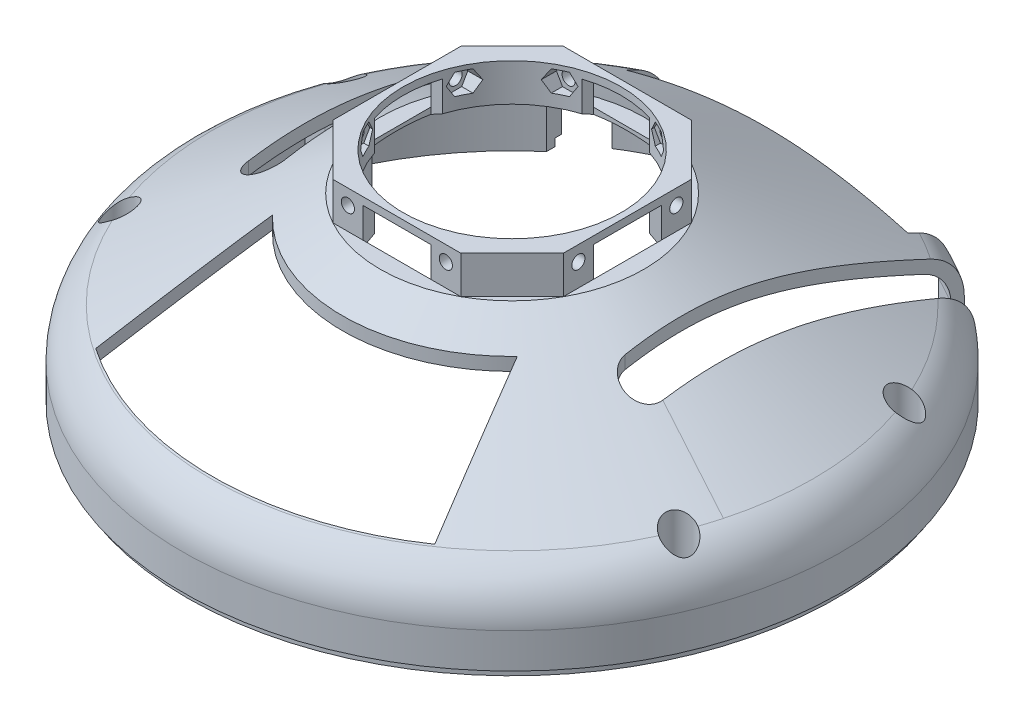
SolidWorks part; units mm, degrees
ref_plane "Front Plane" through (0, 0, 0) normal (0, 0, 1) x (1, 0, 0)
ref_plane "Top Plane" through (0, 0, 0) normal (0, 1, 0) x (1, 0, 0)
ref_plane "Right Plane" through (0, 0, 0) normal (1, 0, 0) x (0, 0, -1)
sketch "Sketch1" plane through (0, 0, 0) normal (0, 0, 1) x (1, 0, 0)
  line L0 (0, 0) -> (-87.5, 0)
  line L1 (-87.5, 0) -> (-87.5, 11.2952)
  line L2 (-79.9421, 24.3188) -> (-35, 50)
  line L3 (-35, 50) -> (0, 50)
  line L4 (0, 50) -> (0, 0)
  arc A0 (-87.5, 11.2952) -> (-79.9421, 24.3188) centre (-72.5, 11.2952) cw
  point P8 (-87.5, 20)
  dimension "D5" = 15
  dimension "D1" = 87.5
  dimension "D2" = 50
  dimension "D3" = 20
  dimension "D4" = 35
revolve "Revolve1" add sketch "Sketch1" angle 360 about L4
shell "Shell2" thickness 3
sketch "Sketch4" plane through (0, 0, 0) normal (0, 1, 0) x (1, 0, 0)
  line L1 (-37.5, 107.5) -> (37.5, 107.5)
  line L2 (-37.5, 107.5) -> (-37.5, 67.5)
  line L3 (-37.5, 67.5) -> (37.5, 67.5)
  line L4 (37.5, 107.5) -> (37.5, 67.5)
  line L5 (-37.5, 107.5) -> (37.5, 67.5) construction
  line L6 (-37.5, 67.5) -> (37.5, 107.5) construction
  circle A0 centre (0, 0) radius 87.5 construction
  point P0 (0, 87.5)
  dimension "D1" = 75
  dimension "D2" = 40
extrude "Cut-Extrude2" cut sketch "Sketch4" along normal through all
sketch "Sketch5" plane through (0, 0, 0) normal (0, -1, 0) x (1, 0, 0)
  circle A0 centre (0, 0) radius 86
  arc A1 (37.5, -79.0569) -> (-37.5, -79.0569) centre (0, 0) ccw construction
  dimension "D1" = 1.5
extrude "Cut-Extrude3" cut sketch "Sketch5" against normal blind 2
sketch "Sketch7" plane through (0, 0, 0) normal (0, -1, 0) x (1, 0, 0)
  line L0 (-74.1747, 29.9685) -> (0, 0) construction
  line L1 (0, 0) -> (-74.1747, 0) construction
  line L2 (-71.0454, 33.8682) -> (-75.68, 37.5872)
  line L3 (-75.68, 37.5872) -> (-80.5498, 25.5338) construction
  line L4 (-80.5498, 25.5338) -> (-74.6326, 24.9895)
  line L5 (-78.1149, 31.5605) -> (-74.1747, 29.9685) construction
  circle A0 centre (-74.1747, 29.9685) radius 1.75
  arc A1 (-74.6326, 24.9895) -> (-71.0454, 33.8682) centre (-74.1747, 29.9685) ccw
  arc A3 (-75.68, 37.5872) -> (-80.5498, 25.5338) centre (0, 0) ccw
  arc A4 (37.5, -75.7232) -> (-37.5, -75.7232) centre (0, 0) ccw construction
  point P15 (-74.1747, 0)
  dimension "D2" = 3.5
  dimension "D3" = 10
  dimension "D1" = 80
  dimension "D4" = 22
  dimension "D5" = 13
extrude "Boss-Extrude1" add sketch "Sketch7" against normal up to next
sketch "Sketch8" plane through (0, 50, 0) normal (0, 1, 0) x (1, 0, 0)
  circle A0 centre (-74.1747, -29.9685) radius 4
  circle A1 centre (-74.1747, -29.9685) radius 1.75 construction
  circle A2 centre (-74.1747, -29.9685) radius 1.75 construction
  dimension "D2" = 8
extrude "Cut-Extrude4" cut sketch "Sketch8" against normal blind 43
mirror "Mirror1" about plane through (0, 0, 0) normal (1, 0, 0) of "Boss-Extrude1", "Cut-Extrude4" second plane through (0, 0, 0) second plane normal (0, 0, 1)
sketch "Sketch9" plane through (0, 0, 0) normal (0, 1, 0) x (1, 0, 0)
  line L0 (-50, 82.5) -> (-50, -15) construction
  line L1 (-45, 82.5) -> (-45, -15)
  line L2 (-55, 82.5) -> (-55, -15)
  line L3 (50, -15) -> (50, 82.5) construction
  line L4 (45, -15) -> (45, 82.5)
  line L5 (55, -15) -> (55, 82.5)
  line L6 (-50, 82.5) -> (50, 82.5) construction
  line L7 (-50, -15) -> (50, -15) construction
  line L8 (0, 0) -> (0, -15) construction
  line L9 (37.5, 67.5) -> (-37.5, 67.5) construction
  arc A0 (-45, 82.5) -> (-55, 82.5) centre (-50, 82.5) ccw
  arc A1 (-55, -15) -> (-45, -15) centre (-50, -15) ccw
  arc A2 (45, -15) -> (55, -15) centre (50, -15) ccw
  arc A3 (55, 82.5) -> (45, 82.5) centre (50, 82.5) ccw
  point P2 (-50, 33.75)
  point P7 (50, 33.75)
  dimension "D1" = 100
  dimension "D2" = 15
  dimension "D3" = 10
  dimension "D4" = 15
extrude "Cut-Extrude5" cut sketch "Sketch9" along normal through all
sketch "Sketch10" plane through (0, 0, 0) normal (0, 1, 0) x (1, 0, 0)
  line L0 (-32.5, -31.1247) -> (-45, -65.5382)
  line L1 (-45, -65.5382) -> (45, -65.5382) construction
  line L2 (45, -65.5382) -> (32.5, -31.1247)
  line L3 (32.5, -31.1247) -> (-32.5, -31.1247) construction
  arc A0 (-32.5, -31.1247) -> (32.5, -31.1247) centre (0, 0) ccw
  arc A1 (-45, -65.5382) -> (45, -65.5382) centre (0, 0) ccw
  arc A2 (-55, 68.0533) -> (55, 68.0533) centre (0, 0) ccw construction
  circle A4 centre (0, 0) radius 35 construction
  dimension "D1" = 8
  dimension "D2" = 10
  dimension "D3" = 90
  dimension "D4" = 65
extrude "Cut-Extrude6" cut sketch "Sketch10" along normal through all
sketch "Sketch11" plane through (0, 50, 0) normal (0, 1, 0) x (1, 0, 0)
  line L1 (-17, 30.5941) -> (-30.5941, 17)
  line L2 (-30.5941, 17) -> (-30.5941, -17)
  line L3 (-30.5941, -17) -> (-17, -30.5941)
  line L4 (-17, -30.5941) -> (17, -30.5941)
  line L5 (17, -30.5941) -> (30.5941, -17)
  line L6 (30.5941, -17) -> (30.5941, 17)
  line L7 (30.5941, 17) -> (17, 30.5941)
  line L8 (17, 30.5941) -> (-17, 30.5941)
  circle A0 centre (0, 0) radius 28.9533 construction
  circle A3 centre (0, 0) radius 28.9533
  circle A4 centre (0, 0) radius 35 construction
  dimension "D1" = 34
extrude "Boss-Extrude2" add sketch "Sketch11" along normal blind 10
sketch "Sketch13" plane through (0, 0, 30.5941) normal (0, 0, 1) x (1, 0, 0)
  line L0 (0, 58) -> (0, 60) construction
  line L1 (-9, 58) -> (9, 58)
  line L2 (-9, 58) -> (-9, 48)
  line L3 (-9, 48) -> (9, 48)
  line L4 (9, 58) -> (9, 48)
  line L5 (-9, 58) -> (9, 48) construction
  line L6 (-9, 48) -> (9, 58) construction
  line L7 (-17, 60) -> (17, 60) construction
  line L8 (-13, 56) -> (13, 56) construction
  line L9 (0, 56) -> (0, 58) construction
  circle A0 centre (-13, 56) radius 1.75
  circle A1 centre (13, 56) radius 1.75
  point P0 (0, 53)
  dimension "D2" = 3.5
  dimension "D1" = 26
  dimension "D3" = 4
  dimension "D4" = 2
  dimension "D5" = 18
  dimension "D6" = 10
extrude "Cut-Extrude7" cut sketch "Sketch13" against normal blind 10
sketch "Sketch14" plane through (0, 0, 0) normal (0, 0, 1) x (1, 0, 0)
  line L1 (-9.7668, 56) -> (-11.3834, 58.8)
  line L2 (-11.3834, 58.8) -> (-14.6166, 58.8)
  line L3 (-14.6166, 58.8) -> (-16.2332, 56)
  line L4 (-16.2332, 56) -> (-14.6166, 53.2)
  line L5 (-14.6166, 53.2) -> (-11.3834, 53.2)
  line L6 (-11.3834, 53.2) -> (-9.7668, 56)
  line L7 (16.2332, 56) -> (14.6166, 58.8)
  line L8 (14.6166, 58.8) -> (11.3834, 58.8)
  line L9 (11.3834, 58.8) -> (9.7668, 56)
  line L10 (9.7668, 56) -> (11.3834, 53.2)
  line L11 (11.3834, 53.2) -> (14.6166, 53.2)
  line L12 (14.6166, 53.2) -> (16.2332, 56)
  circle A0 centre (-13, 56) radius 2.8 construction
  circle A1 centre (13, 56) radius 2.8 construction
  dimension "D1" = 5.6
extrude "Cut-Extrude8" cut sketch "Sketch14" along normal blind 28
pattern_circular "CirPattern1" count 4 over 360 about axis through (0, 0, 0) along (0, 1, 0) of "Cut-Extrude7", "Cut-Extrude8"
sketch "Sketch15" plane through (0, 2, 0) normal (0, -1, 0) x (1, 0, 0)
  line L0 (45, -73.2871) -> (45, -71.521) construction
  line L1 (37.5, -75.7232) -> (37.5, -77.3935) construction
  line L2 (-55, -66.1135) -> (-55, -64.1502)
  line L3 (55, -64.1502) -> (55, -66.1135)
  line L4 (-55, -66.1135) -> (-55, -64.1502)
  line L5 (55, -64.1502) -> (55, -66.1135)
  line L6 (-45, -71.521) -> (-45, -73.2871) construction
  line L7 (-37.5, -77.3935) -> (-37.5, -75.7232) construction
  line L8 (45, -73.2871) -> (45, -71.521)
  line L9 (37.5, -75.7232) -> (37.5, -77.3935)
  line L10 (-45, -71.521) -> (-45, -73.2871)
  line L11 (-37.5, -77.3935) -> (-37.5, -75.7232)
  arc A0 (37.5, -77.3935) -> (45, -73.2871) centre (0, 0) ccw construction
  arc A1 (37.5, -75.7232) -> (45, -71.521) centre (0, 0) ccw construction
  arc A2 (-45, -71.521) -> (-37.5, -75.7232) centre (0, 0) ccw construction
  arc A3 (-45, -73.2871) -> (-37.5, -77.3935) centre (0, 0) ccw construction
  arc A4 (37.5, -77.3935) -> (45, -73.2871) centre (0, 0) ccw
  arc A5 (37.5, -75.7232) -> (45, -71.521) centre (0, 0) ccw
  arc A6 (-45, -71.521) -> (-37.5, -75.7232) centre (0, 0) ccw
  arc A7 (-45, -73.2871) -> (-37.5, -77.3935) centre (0, 0) ccw
  arc A9 (55, -66.1135) -> (-55, -66.1135) centre (0, 0) ccw
  arc A10 (-75.68, -37.5872) -> (-55, -64.1502) centre (0, 0) ccw
  arc A11 (-80.5498, -25.5338) -> (-75.68, -37.5872) centre (0, 0) ccw
  arc A12 (-80.5498, 25.5338) -> (-80.5498, -25.5338) centre (0, 0) ccw
  arc A13 (-75.68, 37.5872) -> (-80.5498, 25.5338) centre (0, 0) ccw
  arc A14 (75.68, 37.5872) -> (-75.68, 37.5872) centre (0, 0) ccw
  arc A15 (80.5498, 25.5338) -> (75.68, 37.5872) centre (0, 0) ccw
  arc A16 (80.5498, -25.5338) -> (80.5498, 25.5338) centre (0, 0) ccw
  arc A17 (55, -64.1502) -> (75.68, -37.5872) centre (0, 0) ccw
  arc A18 (55, -66.1135) -> (-55, -66.1135) centre (0, 0) ccw
  arc A19 (-75.68, -37.5872) -> (-55, -64.1502) centre (0, 0) ccw
  arc A20 (-80.5498, -25.5338) -> (-75.68, -37.5872) centre (0, 0) ccw
  arc A21 (-80.5498, 25.5338) -> (-80.5498, -25.5338) centre (0, 0) ccw
  arc A22 (-75.68, 37.5872) -> (-80.5498, 25.5338) centre (0, 0) ccw
  arc A23 (75.68, 37.5872) -> (-75.68, 37.5872) centre (0, 0) ccw
  arc A24 (80.5498, 25.5338) -> (75.68, 37.5872) centre (0, 0) ccw
  arc A25 (80.5498, -25.5338) -> (80.5498, 25.5338) centre (0, 0) ccw
  arc A26 (55, -64.1502) -> (75.68, -37.5872) centre (0, 0) ccw
  arc A28 (75.68, -37.5872) -> (80.5498, -25.5338) centre (0, 0) ccw
  arc A29 (75.68, -37.5872) -> (80.5498, -25.5338) centre (0, 0) ccw
  dimension "D1" = 0
extrude "Boss-Extrude3" add sketch "Sketch15" along normal blind 2
sketch "Sketch16" plane through (0, 0, 0) normal (0, -1, 0) x (1, 0, 0)
  line L0 (55, -64.1502) -> (55, -68.0533) construction
  line L1 (-55, -68.0533) -> (-55, -66.3735)
  line L2 (55, -66.3735) -> (55, -68.0533)
  line L3 (45, -75.0417) -> (45, -71.521) construction
  line L4 (37.5, -75.7232) -> (37.5, -79.0569) construction
  line L5 (-37.5, -79.0569) -> (-37.5, -75.7232) construction
  line L6 (-45, -71.521) -> (-45, -75.0417) construction
  line L7 (45, -75.0417) -> (45, -71.521)
  line L8 (37.5, -75.7232) -> (37.5, -79.0569)
  line L9 (-37.5, -79.0569) -> (-37.5, -75.7232)
  line L10 (-45, -71.521) -> (-45, -75.0417)
  arc A0 (55, -68.0533) -> (-55, -68.0533) centre (0, 0) ccw construction
  arc A1 (55, -68.0533) -> (-55, -68.0533) centre (0, 0) ccw
  arc A2 (55, -66.3735) -> (-55, -66.3735) centre (0, 0) ccw
  arc A3 (54.1829, -67.0422) -> (-54.1829, -67.0422) centre (0, 0) ccw construction
  arc A4 (37.5, -79.0569) -> (45, -75.0417) centre (0, 0) ccw construction
  arc A5 (37.5, -75.7232) -> (45, -71.521) centre (0, 0) ccw construction
  arc A6 (-45, -71.521) -> (-37.5, -75.7232) centre (0, 0) ccw construction
  arc A7 (-45, -75.0417) -> (-37.5, -79.0569) centre (0, 0) ccw construction
  arc A8 (37.5, -79.0569) -> (45, -75.0417) centre (0, 0) ccw
  arc A9 (37.5, -75.7232) -> (45, -71.521) centre (0, 0) ccw
  arc A10 (-45, -71.521) -> (-37.5, -75.7232) centre (0, 0) ccw
  arc A11 (-45, -75.0417) -> (-37.5, -79.0569) centre (0, 0) ccw
  dimension "D1" = 1.3
extrude "Cut-Extrude9" cut sketch "Sketch16" against normal blind 2
